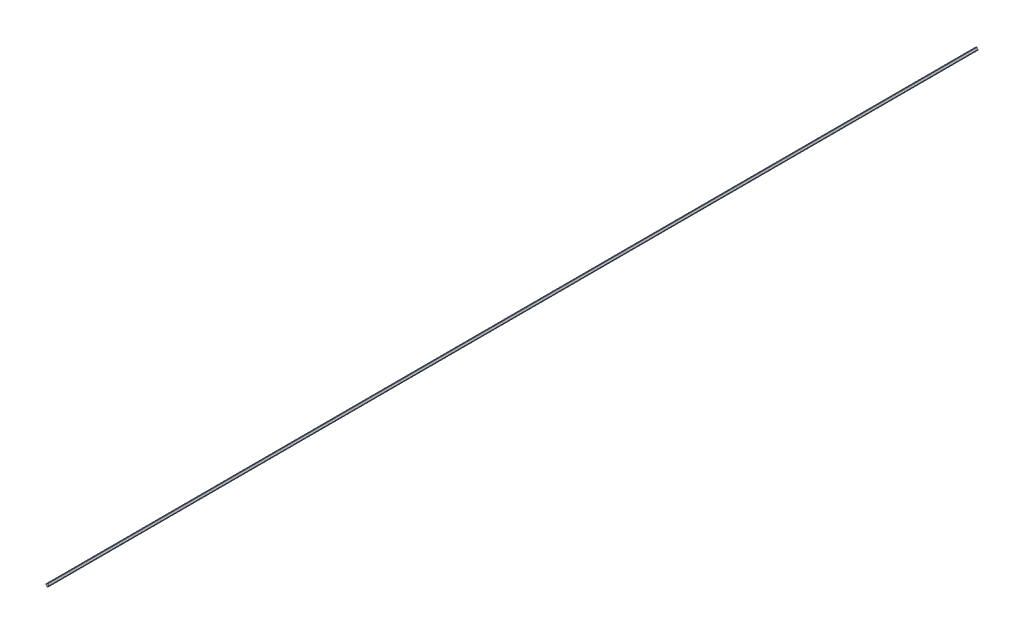
SolidWorks part; units mm, degrees
material "Water"
ref_plane "Front Plane" through (0, 0, 0) normal (0, 0, 1) x (1, 0, 0)
ref_plane "Top Plane" through (0, 0, 0) normal (0, 1, 0) x (1, 0, 0)
ref_plane "Right Plane" through (0, 0, 0) normal (1, 0, 0) x (0, 0, -1)
sketch "Sketch1" plane through (0, 0, 0) normal (0, 0, 1) x (1, 0, 0)
  line L0 (1.545, 7.135) -> (-1.545, 7.135)
  line L1 (-7.135, 1.545) -> (-7.135, -1.545)
  line L2 (-7.135, 0) -> (0, 0) construction
  line L3 (0, 0) -> (0, 7.135) construction
  line L4 (7.135, 1.545) -> (7.135, -1.545)
  line L5 (1.545, -7.135) -> (-1.545, -7.135)
  arc A0 (-1.545, 7.135) -> (-7.135, 1.545) centre (-7.135, 7.135) cw
  arc A2 (1.545, 7.135) -> (7.135, 1.545) centre (7.135, 7.135) ccw
  arc A3 (1.545, -7.135) -> (7.135, -1.545) centre (7.135, -7.135) cw
  arc A4 (-1.545, -7.135) -> (-7.135, -1.545) centre (-7.135, -7.135) ccw
  point P5 (-13.3161, 7.4157)
  point P19 (7.135, 0)
  dimension "D3" = 5.59
  dimension "D1" = 14.27
  dimension "D2" = 14.27
  dimension "D4" = 7.135
  dimension "D5" = 7.135
extrude "Boss-Extrude1" add sketch "Sketch1" along normal mid plane 4178.7
